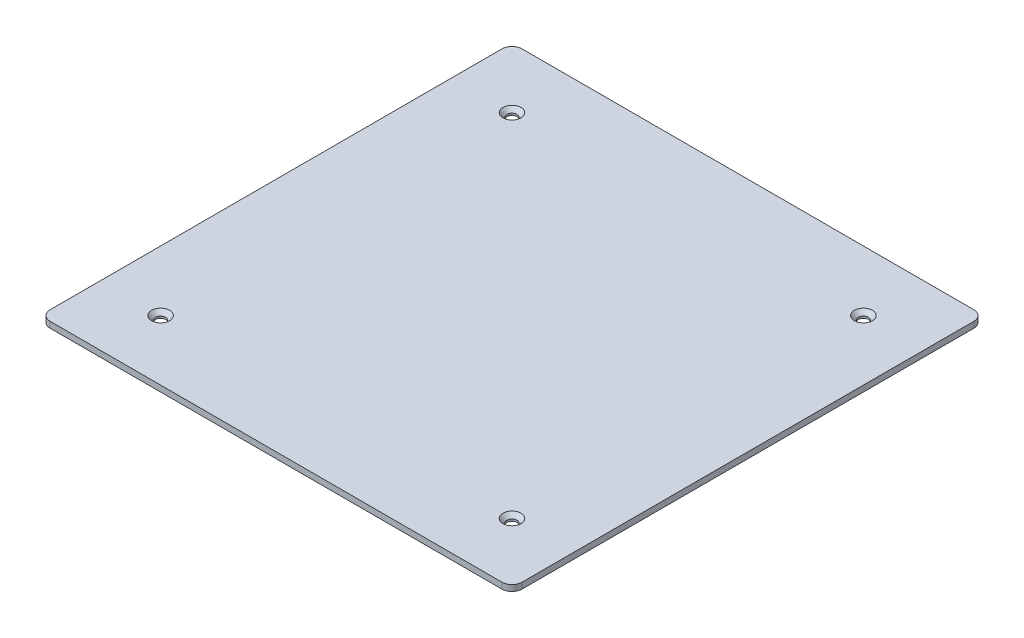
SolidWorks part; units mm, degrees
ref_plane "Plan de face" through (0, 0, 0) normal (0, 0, 1) x (1, 0, 0)
ref_plane "Plan de dessus" through (0, 0, 0) normal (0, 1, 0) x (1, 0, 0)
ref_plane "Plan de droite" through (0, 0, 0) normal (1, 0, 0) x (0, 0, -1)
sketch "Esquisse1" plane through (0, 0, 0) normal (0, 1, 0) x (1, 0, 0)
  line L1 (112.5, -117.5) -> (-112.5, -117.5)
  line L2 (117.5, -112.5) -> (117.5, 112.5)
  line L3 (112.5, 117.5) -> (-112.5, 117.5)
  line L4 (-117.5, -112.5) -> (-117.5, 112.5)
  circle A0 centre (-87.5, 87.5) radius 2.5
  circle A1 centre (-87.5, -87.5) radius 2.5
  circle A2 centre (87.5, -87.5) radius 2.5
  circle A3 centre (87.5, 87.5) radius 2.5
  arc A4 (112.5, -117.5) -> (117.5, -112.5) centre (112.5, -112.5) ccw
  arc A5 (117.5, 112.5) -> (112.5, 117.5) centre (112.5, 112.5) ccw
  arc A6 (-112.5, -117.5) -> (-117.5, -112.5) centre (-112.5, -112.5) cw
  arc A7 (-112.5, 117.5) -> (-117.5, 112.5) centre (-112.5, 112.5) ccw
  point P0 (0, 0)
  point P18 (117.5, 117.5)
  point P23 (-117.5, 117.5)
  dimension "D3" = 5
  dimension "D4" = 5
  dimension "D5" = 5
  dimension "D6" = 5
  dimension "D2" = 5
  dimension "D1" = 235
  dimension "D7" = 87.5
  dimension "D8" = 117.5
  dimension "D9" = 87.5
extrude "Boss.-Extru.1" add sketch "Esquisse1" along normal blind 3
chamfer "Chanfrein1" distance 2 angle 45 4 edges at (87.5, 3, -85) (87.5, 3, 90) (-87.5, 3, 90) (-87.5, 3, -85)
